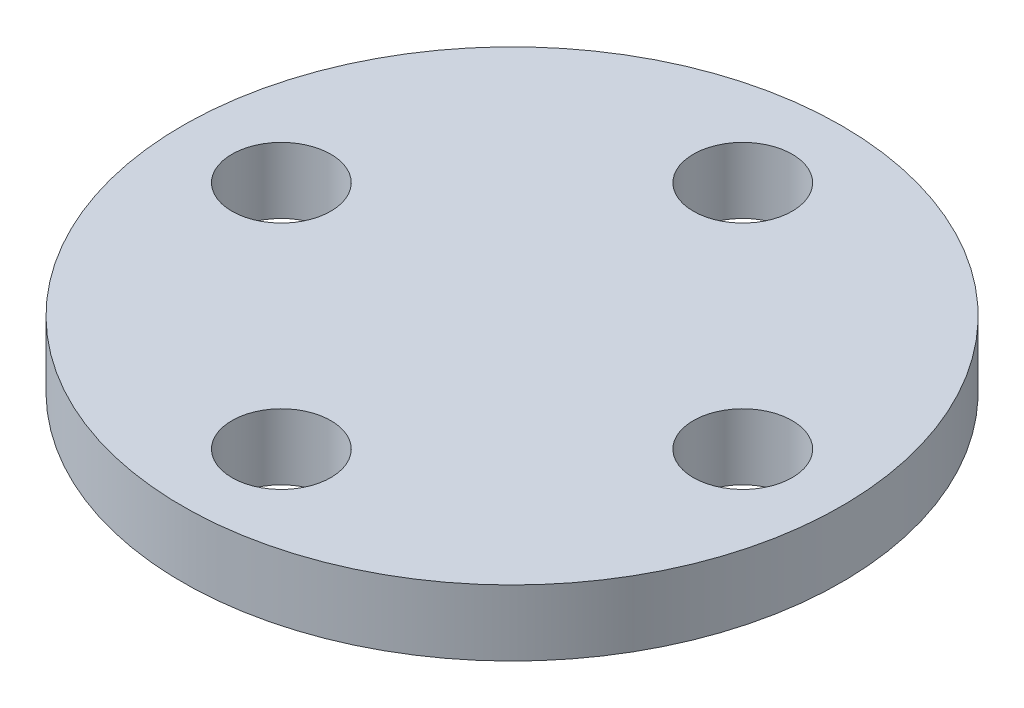
SolidWorks part; units mm, degrees
ref_plane "前视基准面" through (0, 0, 0) normal (0, 0, 1) x (1, 0, 0)
ref_plane "上视基准面" through (0, 0, 0) normal (0, 1, 0) x (1, 0, 0)
ref_plane "右视基准面" through (0, 0, 0) normal (1, 0, 0) x (0, 0, -1)
other "Configuration Table"
sketch "草图1" plane through (0, 0, 0) normal (0, 0, 1) x (1, 0, 0)
  line L5 (0, 4.5) -> (-10, 4.5)
  line L6 (-10, 4.5) -> (-10, 2.5)
  line L7 (-10, 2.5) -> (-4.5, 2.5)
  line L8 (-4.5, 2.5) -> (-4.5, 0)
  line L9 (-4.5, 0) -> (-2.75, 0)
  line L10 (-2.75, 0) -> (-2.75, 3.5)
  line L11 (-2.75, 3.5) -> (0, 3.5)
  line L12 (0, 3.5) -> (0, 4.5)
  line L13 (0, 0) -> (0, 1.3716) construction
  point P1 (0, 5.2)
  point P2 (-0.2149, 5.2)
  dimension "D1" = 5.5
  dimension "D2" = 9
  dimension "D3" = 20
  dimension "D4" = 1
  dimension "D5" = 4.5
  dimension "D6" = 2
revolve "旋转1" add sketch "草图1" angle 360 about L13
sketch "草图2" plane through (0, 4.5, 0) normal (0, 1, 0) x (1, 0, 0)
  line L0 (0, 0) -> (0, 4.1078) construction
  circle A0 centre (0, 7) radius 1.5
  circle A1 centre (7, 0) radius 1.5
  circle A2 centre (0, -7) radius 1.5
  circle A3 centre (-7, 0) radius 1.5
  point P14 (0, 0)
  dimension "D1" = 3
  dimension "D2" = 7
  dimension "D3" = 4
extrude "切除-拉伸1" cut sketch "草图2" against normal up to next
